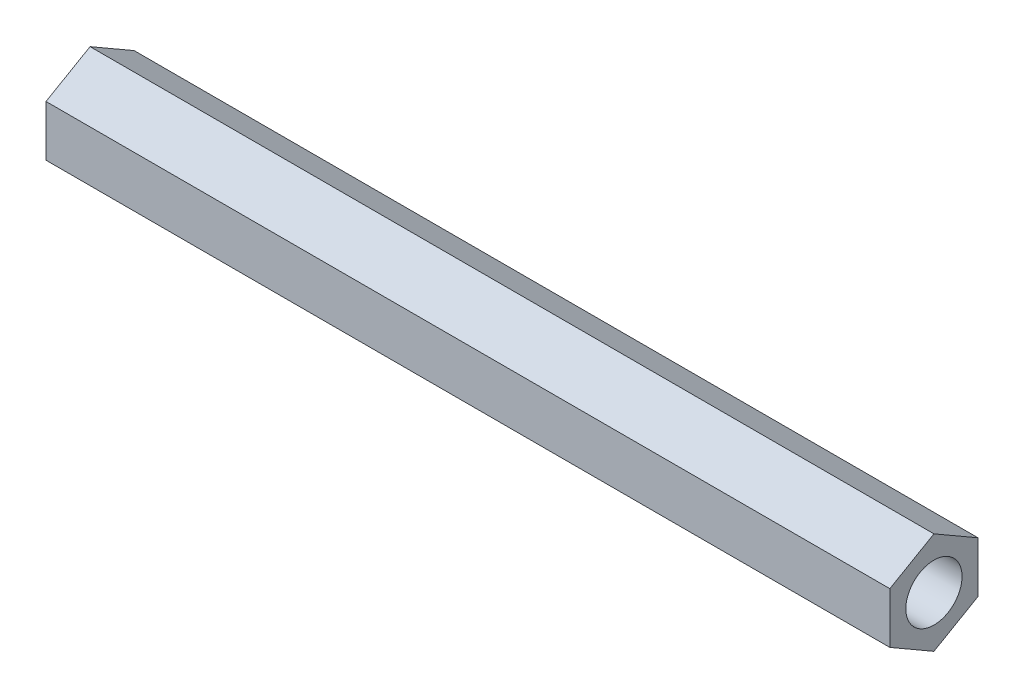
SolidWorks part; units mm, degrees
ref_plane "前视基准面" through (0, 0, 0) normal (0, 0, 1) x (1, 0, 0)
ref_plane "上视基准面" through (0, 0, 0) normal (0, 1, 0) x (1, 0, 0)
ref_plane "右视基准面" through (0, 0, 0) normal (1, 0, 0) x (0, 0, -1)
sketch "草图1" plane through (0, 0, 0) normal (1, 0, 0) x (0, 0, -1)
  line L1 (2.35, 1.3568) -> (0, 2.7135)
  line L2 (0, 2.7135) -> (-2.35, 1.3568)
  line L3 (-2.35, 1.3568) -> (-2.35, -1.3568)
  line L4 (-2.35, -1.3568) -> (0, -2.7135)
  line L5 (0, -2.7135) -> (2.35, -1.3568)
  line L6 (2.35, -1.3568) -> (2.35, 1.3568)
  circle A0 centre (0, 0) radius 2.35 construction
  circle A1 centre (0, 0) radius 1.5
  dimension "D2" = 3
  dimension "D1" = 4.7
extrude "凸台-拉伸1" add sketch "草图1" along normal blind 45
